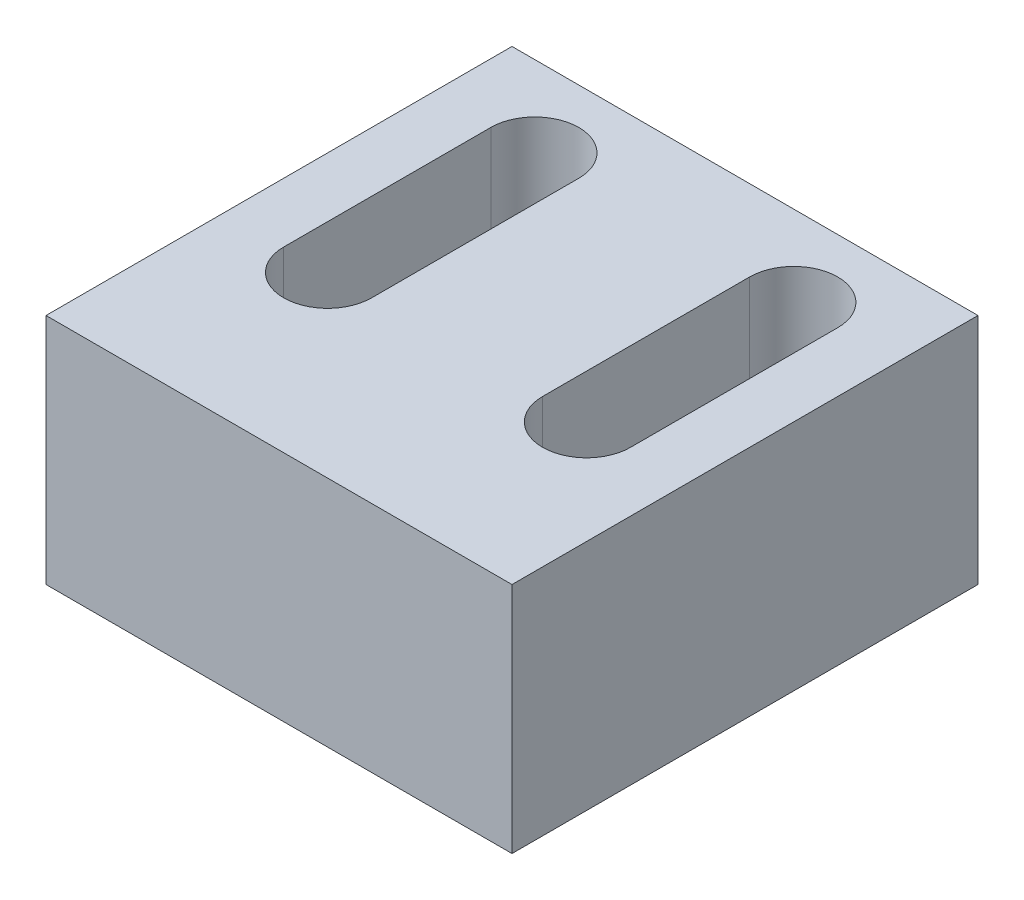
SolidWorks part; units mm, degrees
ref_plane "Front Plane" through (0, 0, 0) normal (0, 0, 1) x (1, 0, 0)
ref_plane "Top Plane" through (0, 0, 0) normal (0, 1, 0) x (1, 0, 0)
ref_plane "Right Plane" through (0, 0, 0) normal (1, 0, 0) x (0, 0, -1)
sketch "Sketch1" plane through (0, 0, 0) normal (1, 0, 0) x (0, 0, -1)
  line L1 (-22.5, 11.25) -> (22.5, 11.25)
  line L2 (-22.5, 11.25) -> (-22.5, -11.25)
  line L3 (-22.5, -11.25) -> (22.5, -11.25)
  line L4 (22.5, 11.25) -> (22.5, -11.25)
  line L5 (-22.5, 11.25) -> (22.5, -11.25) construction
  line L6 (-22.5, -11.25) -> (22.5, 11.25) construction
  point P0 (0, 0)
  dimension "D1" = 45
  dimension "D2" = 22.5
extrude "Boss-Extrude1" add sketch "Sketch1" along normal mid plane 45
sketch "Sketch2" plane through (0, 11.25, 0) normal (0, 1, 0) x (1, 0, 0)
  line L0 (0, 22.5) -> (0, -22.5) construction
  line L1 (22.5, 22.5) -> (-22.5, 22.5) construction
  line L2 (22.5, -22.5) -> (-22.5, -22.5) construction
  line L3 (-12.5, 14.7) -> (-12.5, -5.3) construction
  line L4 (-8.25, 14.7) -> (-8.25, -5.3)
  line L5 (-16.75, 14.7) -> (-16.75, -5.3)
  line L6 (12.5, 14.7) -> (12.5, -5.3) construction
  line L7 (8.25, 14.7) -> (8.25, -5.3)
  line L8 (16.75, 14.7) -> (16.75, -5.3)
  arc A0 (-8.25, 14.7) -> (-16.75, 14.7) centre (-12.5, 14.7) ccw
  arc A1 (-16.75, -5.3) -> (-8.25, -5.3) centre (-12.5, -5.3) ccw
  arc A2 (8.25, 14.7) -> (16.75, 14.7) centre (12.5, 14.7) cw
  arc A3 (16.75, -5.3) -> (8.25, -5.3) centre (12.5, -5.3) cw
  point P8 (-12.5, 4.7)
  point P15 (0, 14.6085)
  point P16 (12.5, 4.7)
  dimension "D2" = 4.25
  dimension "D1" = 20
  dimension "D3" = 7.8
  dimension "D4" = 25
extrude "Cut-Extrude1" cut sketch "Sketch2" against normal blind 45
